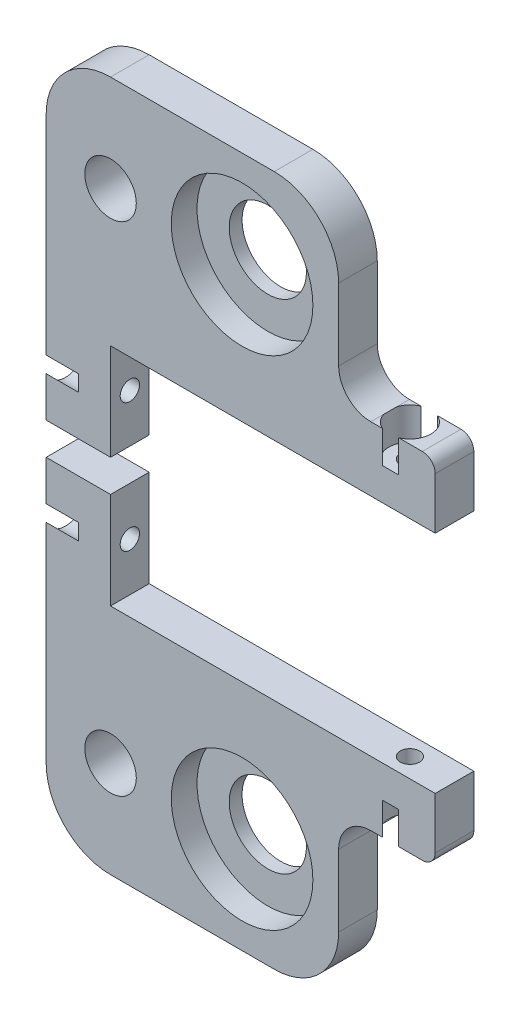
SolidWorks part; units mm, degrees
ref_plane "Alzado" through (0, 0, 0) normal (0, 0, 1) x (1, 0, 0)
ref_plane "Planta" through (0, 0, 0) normal (0, 1, 0) x (1, 0, 0)
ref_plane "Vista lateral" through (0, 0, 0) normal (1, 0, 0) x (0, 0, -1)
sketch "Croquis1" plane through (0, 0, 0) normal (0, 0, 1) x (1, 0, 0)
  line L0 (-50.43, 0) -> (0, 0)
  line L1 (0, 0) -> (0, -8)
  line L2 (-2, -10) -> (-10, -10)
  line L3 (-15, -15) -> (-15, -26.15)
  line L4 (-25, -36.15) -> (-50.43, -36.15)
  line L5 (-60.43, -26.15) -> (-60.43, 15)
  line L6 (-60.43, 15) -> (-50.43, 15)
  line L7 (-50.43, 15) -> (-50.43, 0)
  circle A0 centre (-50.43, -21.15) radius 4
  circle A1 centre (-30, -21.15) radius 6
  circle A2 centre (-30, -21.15) radius 11
  arc A3 (-50.43, -36.15) -> (-60.43, -26.15) centre (-50.43, -26.15) cw
  arc A4 (-25, -36.15) -> (-15, -26.15) centre (-25, -26.15) ccw
  arc A5 (-15, -15) -> (-10, -10) centre (-10, -15) cw
  arc A6 (0, -8) -> (-2, -10) centre (-2, -8) cw
  dimension "D1" = 8
  dimension "D3" = 20.43
  dimension "D4" = 12
  dimension "D7" = 22
  dimension "D14" = 10
  dimension "D15" = 10
  dimension "D16" = 5
  dimension "D17" = 2
  dimension "D2" = 10
  dimension "D5" = 10
  dimension "D8" = 21.15
  dimension "D9" = 15
  dimension "D10" = 15
  dimension "D11" = 10
  dimension "D12" = 15
  dimension "D13" = 15
extrude "Saliente-Extruir2" add sketch "Croquis1" along normal blind 6 contours A1 | A0 | L4 A3 L5 L6 L7 L0 L1 A6 L2 A5 L3 A4
sketch "Croquis2" plane through (0, 0, 6) normal (0, 0, 1) x (1, 0, 0)
  circle A0 centre (-30, -21.15) radius 11
  dimension "D1" = 22
extrude "Cortar-Extruir1" cut sketch "Croquis2" against normal blind 4
sketch "Croquis3" plane through (0, 0, 0) normal (0, 1, 0) x (-1, 0, 0)
  line L1 (50.43, 0) -> (0, 0) construction
  line L2 (50.43, 6) -> (50.43, 0) construction
  circle A0 centre (6.93, 3) radius 1.5
  dimension "D1" = 3
  dimension "D3" = 3
  dimension "D2" = 43.5
extrude "Cortar-Extruir2" cut sketch "Croquis3" against normal through all
sketch "Croquis4" plane through (-50.43, 0, 0) normal (1, 0, 0) x (0, 0, -1)
  line L0 (-6, 15) -> (0, 15) construction
  line L1 (-6, 15) -> (-6, 0) construction
  circle A0 centre (-3, 7.5) radius 1.5
  dimension "D1" = 7.5
  dimension "D2" = 3
  dimension "D3" = 3
extrude "Cortar-Extruir3" cut sketch "Croquis4" against normal through all
sketch "Croquis5" plane through (-60.43, 0, 0) normal (-1, 0, 0) x (0, 0, 1)
  circle A0 centre (3, 7.5) radius 3.25
  dimension "D1" = 6.5
extrude "Cortar-Extruir4" cut sketch "Croquis5" against normal blind 5
sketch "Croquis6" plane through (0, -10, 0) normal (0, -1, 0) x (1, 0, 0)
  circle A0 centre (-6.93, 3) radius 3.25
  dimension "D1" = 6.5
extrude "Cortar-Extruir5" cut sketch "Croquis6" against normal blind 5
ref_plane "Plano1" through (0, 17.5, 0) normal (0, 1, 0) x (1, 0, 0)
mirror "Simetría2" about plane through (0, 17.5, 0) normal (0, 1, 0) of bodies 108
